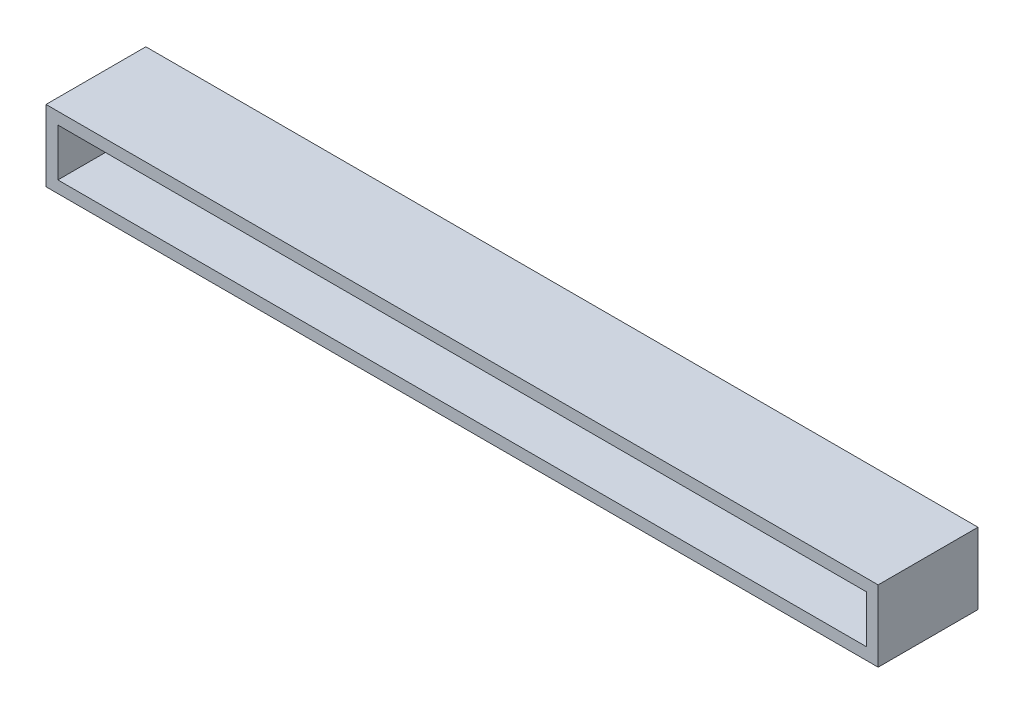
SolidWorks part; units mm, degrees
ref_plane "Front Plane" through (0, 0, 0) normal (0, 0, 1) x (1, 0, 0)
ref_plane "Top Plane" through (0, 0, 0) normal (0, 1, 0) x (1, 0, 0)
ref_plane "Right Plane" through (0, 0, 0) normal (1, 0, 0) x (0, 0, -1)
sketch "Sketch1" plane through (0, 0, 0) normal (0, 0, 1) x (1, 0, 0)
  line L1 (0, 0) -> (177.8, 0)
  line L2 (0, 0) -> (0, 15.24)
  line L3 (0, 15.24) -> (177.8, 15.24)
  line L4 (177.8, 0) -> (177.8, 15.24)
  dimension "D1" = 177.8
  dimension "D2" = 15.24
extrude "Boss-Extrude1" add sketch "Sketch1" along normal blind 2.54
sketch "Sketch2" plane through (0, 0, 2.54) normal (0, 0, 1) x (1, 0, 0)
  line L0 (2.54, 12.7) -> (2.54, 2.54)
  line L1 (0, 15.24) -> (177.8, 15.24)
  line L2 (0, 15.24) -> (0, 0)
  line L3 (0, 0) -> (177.8, 0)
  line L4 (177.8, 15.24) -> (177.8, 0)
  line L5 (2.54, 2.54) -> (175.26, 2.54)
  line L6 (175.26, 12.7) -> (175.26, 2.54)
  line L7 (2.54, 12.7) -> (175.26, 12.7)
  dimension "D1" = 2.54
extrude "Boss-Extrude2" add sketch "Sketch2" along normal blind 18.796
